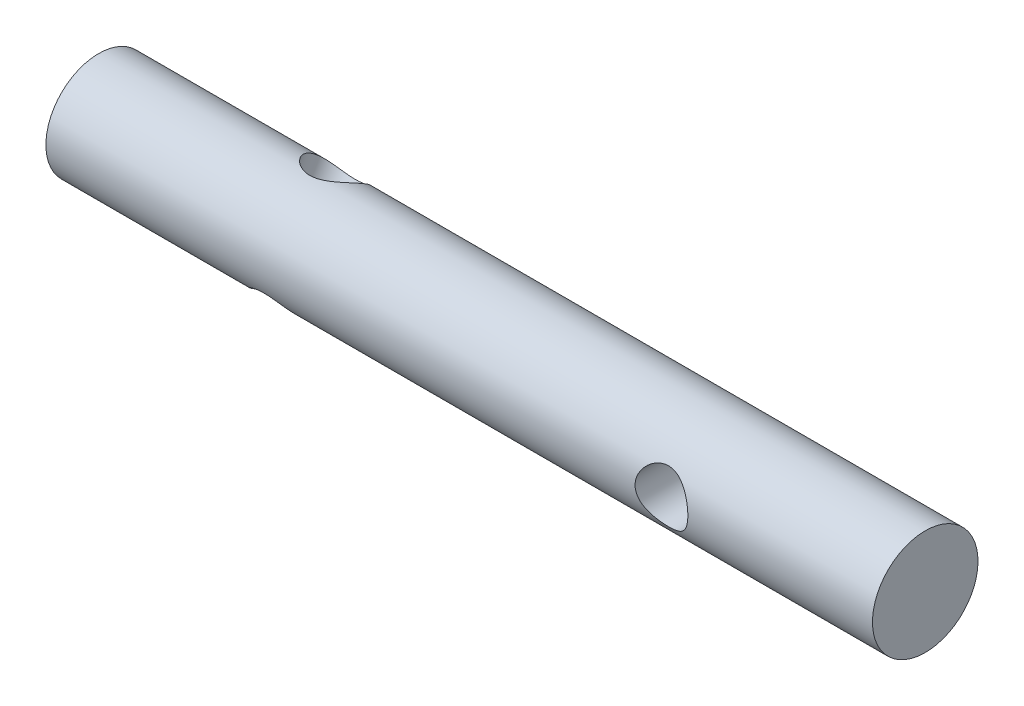
SolidWorks part; units mm, degrees
ref_plane "Front Plane" through (0, 0, 0) normal (1, 0, 0) x (0, 1, 0)
ref_plane "Top Plane" through (0, 0, 0) normal (0, 0, 1) x (0, 1, 0)
ref_plane "Right Plane" through (0, 0, 0) normal (0, 1, 0) x (-1, 0, 0)
sketch "Sketch1" plane through (0, 0, 0) normal (1, 0, 0) x (0, 1, 0)
  circle A0 centre (0, 0) radius 3
  dimension "D1" = 6
extrude "Boss-Extrude1" add sketch "Sketch1" along normal mid plane 47
sketch "Sketch2" plane through (0, 0, 0) normal (0, 0, 1) x (0, 1, 0)
  line L1 (-3, -23.5) -> (3, -23.5) construction
  circle A0 centre (0, -11.5) radius 1.5
  dimension "D1" = 3
  dimension "D4" = 12
extrude "Cut-Extrude1" cut sketch "Sketch2" against normal through all both and the other way through all
ref_plane "Plane2" through (0, 0, 0) normal (0, 0.866, -0.5) x (-1, 0, 0)
sketch "Sketch3" plane through (0, 0, 0) normal (0, 0.866, -0.5) x (-1, 0, 0)
  line L0 (-23.5, 0) -> (23.5, 0) construction
  line L1 (23.5, -3) -> (23.5, 3) construction
  circle A0 centre (11.5, 0) radius 1.5
  dimension "D1" = 3
  dimension "D2" = 12
extrude "Cut-Extrude2" cut sketch "Sketch3" against normal through all both and the other way through all
